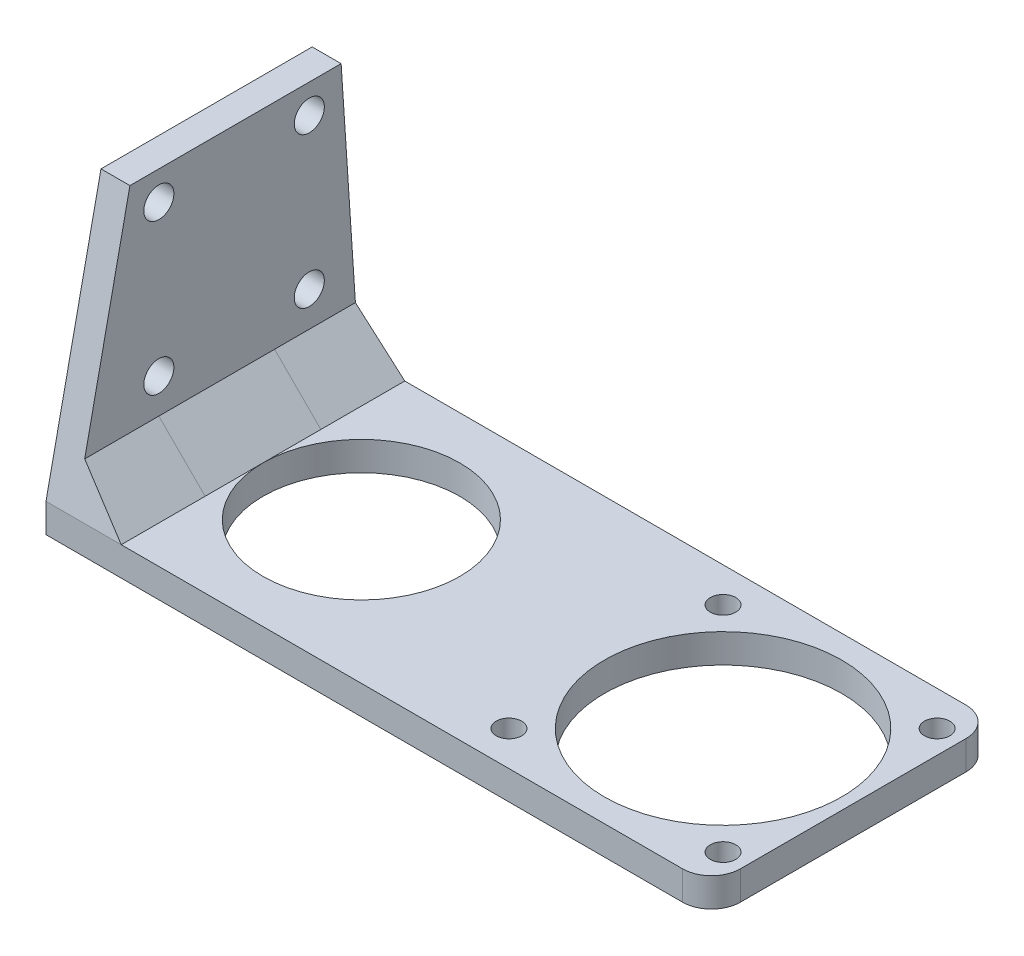
SolidWorks part; units mm, degrees
ref_plane "Front Plane" through (0, 0, 0) normal (0, 0, 1) x (1, 0, 0)
ref_plane "Top Plane" through (0, 0, 0) normal (0, 1, 0) x (1, 0, 0)
ref_plane "Right Plane" through (0, 0, 0) normal (1, 0, 0) x (0, 0, -1)
sketch "Sketch1" plane through (0, 0, 0) normal (0, 1, 0) x (1, 0, 0)
  line L1 (-22.5, 22.5) -> (22.5, 22.5)
  line L2 (-22.5, 22.5) -> (-22.5, -22.5)
  line L3 (-22.5, -22.5) -> (22.5, -22.5)
  line L4 (22.5, 22.5) -> (22.5, -22.5)
  line L5 (-22.5, 22.5) -> (22.5, -22.5) construction
  line L6 (-22.5, -22.5) -> (22.5, 22.5) construction
  circle A0 centre (0, 0) radius 20.5
  point P0 (0, 0)
  dimension "D3" = 41
  dimension "D1" = 45
  dimension "D2" = 45
extrude "Boss-Extrude1" add sketch "Sketch1" along normal blind 5
sketch "Sketch2" plane through (0, 0, 0) normal (0, 1, 0) x (1, 0, 0)
  line L0 (0, 23.8406) -> (0, -24.1143) construction
  line L1 (0, -2.75) -> (0, 2.75) construction
  line L2 (-23.396, 0) -> (23.5328, 0) construction
  line L3 (-2.75, 0) -> (2.75, 0) construction
  circle A0 centre (18.5, 18.5) radius 2.2
  circle A1 centre (18.5, -18.5) radius 2.2
  circle A2 centre (-18.5, 18.5) radius 2.2
  circle A3 centre (-18.5, -18.5) radius 2.2
  dimension "D1" = 4.4
  dimension "D2" = 18.5
  dimension "D3" = 18.5
extrude "Cut-Extrude1" cut sketch "Sketch2" along normal up to next
sketch "Sketch3" plane through (0, 0, 0) normal (0, 1, 0) x (1, 0, 0)
  line L0 (22.5, 22.5) -> (22.5, 24.5)
  line L1 (22.5, 24.5) -> (-92.5, 24.5)
  line L2 (-92.5, 24.5) -> (-92.5, -24.5)
  line L3 (-92.5, -24.5) -> (22.5, -24.5)
  line L4 (22.5, -24.5) -> (22.5, -22.5)
  line L5 (22.5, -22.5) -> (22.5, 22.5) construction
  line L6 (22.5, -22.5) -> (-22.5, -22.5)
  line L7 (-22.5, -22.5) -> (-22.5, 22.5)
  line L8 (-22.5, 22.5) -> (-22.5, -22.5) construction
  line L9 (22.5, 22.5) -> (-22.5, 22.5) construction
  line L10 (-22.5, 22.5) -> (22.5, 22.5)
  dimension "D1" = 2
  dimension "D2" = 2
  dimension "D3" = 115
extrude "Boss-Extrude2" add sketch "Sketch3" along normal blind 5
sketch "Sketch5" plane through (-92.5, 0, 0) normal (-1, 0, 0) x (0, 0, 1)
  line L0 (-24.5, 5) -> (-21.5, 50)
  line L1 (-21.5, 50) -> (15, 50)
  line L2 (-24.5, 5) -> (-24.5, 0)
  line L3 (-24.5, 0) -> (24.5, 0)
  line L4 (24.5, 0) -> (24.5, 5)
  line L5 (26.95, 0) -> (-26.95, 0) construction
  line L6 (15, 50) -> (24.5, 5)
  dimension "D1" = 50
  dimension "D2" = 36.5
  dimension "D3" = 9.5
extrude "Boss-Extrude4" add sketch "Sketch5" against normal blind 5 separate body
sketch "Sketch6" plane through (-87.5, 0, 0) normal (1, 0, 0) x (0, 0, -1)
  line L0 (-15, 50) -> (21.5, 50) construction
  line L1 (0, 27.5) -> (0, -27.5) construction
  line L2 (3, 51.4307) -> (3, -7.6771) construction
  circle A0 centre (16, 45) radius 2.6
  circle A1 centre (16, 19) radius 2.6
  circle A2 centre (-10, 19) radius 2.6
  circle A3 centre (-10, 45) radius 2.6
  dimension "D1" = 5.2
  dimension "D2" = 5.2
  dimension "D3" = 26
  dimension "D4" = 13
  dimension "D5" = 5
  dimension "D6" = 13
  dimension "D7" = 3
extrude "Cut-Extrude2" cut sketch "Sketch6" against normal up to next (5 mm away)
sketch "Sketch7" plane through (0, 0, 0) normal (0, 1, 0) x (1, 0, 0)
  line L0 (-27.5, 0) -> (27.5, 0) construction
  line L1 (-92.5, -15) -> (-92.5, 21.5) construction
  circle A0 centre (-62.5, 0) radius 17
  dimension "D1" = 34
  dimension "D2" = 30
extrude "Cut-Extrude3" cut sketch "Sketch7" along normal up to next (5 mm away)
sketch "Sketch8" plane through (0, 0, 0) normal (0, 0, 1) x (1, 0, 0)
  line L0 (-87.5, 5) -> (-87.5, 13)
  line L1 (-87.5, 5) -> (-87.5, 50) construction
  line L2 (-87.5, 13) -> (-79.5, 5)
  line L3 (-92.5, 5) -> (22.5, 5) construction
  line L4 (-79.5, 5) -> (-87.5, 5)
  dimension "D1" = 8
  dimension "D2" = 8
extrude "Boss-Extrude5" add sketch "Sketch8" along normal mid plane 20
chamfer "Chamfer1" distance 8 angle 45 2 edges at (-87.5, 5, -17.25) (-87.5, 5, 17.25)
fillet "Fillet1" radius 5 2 edges at (22.5, 2.5, -24.5) (22.5, 2.5, 24.5)
